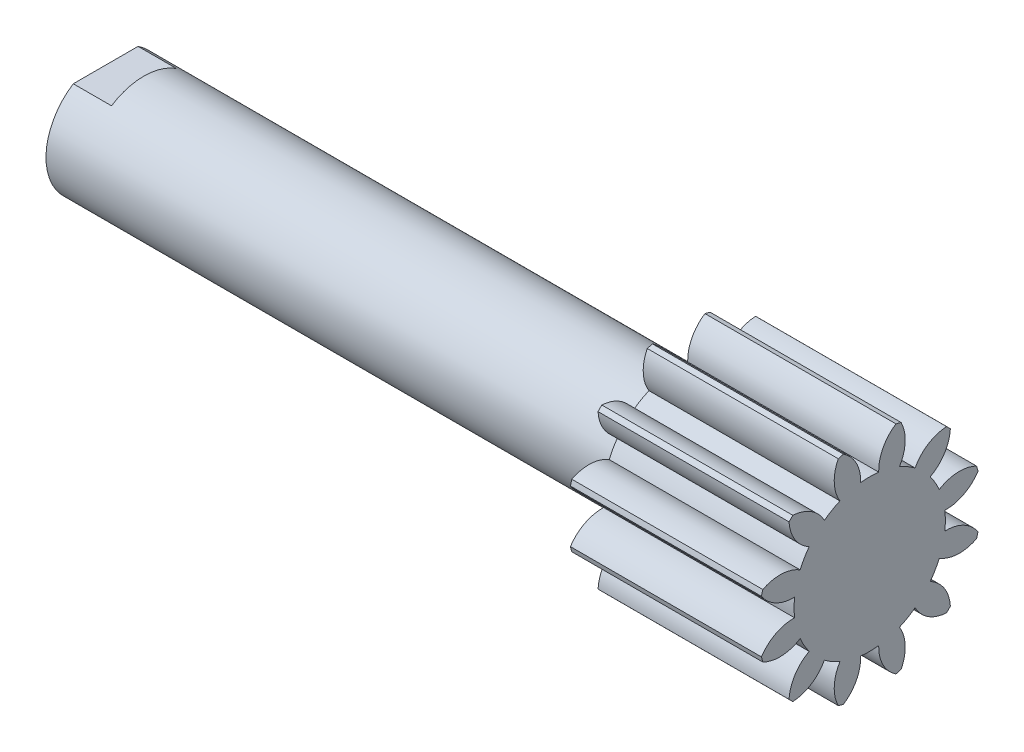
SolidWorks part; units mm, degrees
ref_plane "Plane1" through (0, 0, 0) normal (0, 0, 1) x (1, 0, 0)
ref_plane "Plane2" through (0, 0, 0) normal (0, 1, 0) x (1, 0, 0)
ref_plane "Plane3" through (0, 0, 0) normal (1, 0, 0) x (0, 0, -1)
sketch "HoldingSke" plane through (0, 0, 0) normal (0, 1, 0) x (1, 0, 0)
  line L0 (0, 0) -> (596.2788, -126.743)
  line L1 (-15, 0) -> (100, 0) construction
  line L2 (0, 0) -> (-2.1039, 2.3779)
  line L3 (0, 0) -> (-11.863, 4.5341)
  line L4 (0, 0) -> (8.4473, 1.7955)
  line L5 (0, 0) -> (-47.5972, -17.7524)
  line L6 (0, 0) -> (-10.5278, -7.1032)
  line L7 (-2.1039, 2.3779) -> (8.8314, 51.9901)
  line L8 (-76.2, 54.61) -> (-69.596, 54.61)
  line L9 (-71.009, 38.7566) -> (-53.1078, 45.2721)
  line L10 (-76.2, 71.12) -> (104.1128, 71.12)
  line L11 (0, 0) -> (-12.7, 0)
  line L12 (-76.2, 101.6) -> (-76.1573, 101.6)
  line L13 (24.9733, 27.94) -> (52.9518, 28.4284)
  line L14 (24.9733, 27.94) -> (25.0241, 27.9398)
  line L15 (24.9733, 27.94) -> (100.4021, 29.52)
  circle A0 centre (0, 0) radius 3.175
  circle A1 centre (0, 0) radius 5.0292
  circle A2 centre (0, 0) radius 25.4
  circle A3 centre (0, 0) radius 3.175
  dimension "MHD" = 10.0584
  dimension "Hub_dia" = 50.8
  dimension "Bore" = 6.35
  dimension "MBD" = 6.35
  dimension "Num_teeth" = 12
  dimension "Pitch_radius" = 180.3128
  dimension "Pitch" = 609.6
  dimension "Width" = 12.7
  dimension "Overall_len" = 50.8
  dimension "Show_teeth" = 12
  dimension "Thickness" = 12.7
  dimension "OAL" = 50.8031
  dimension "T_dim" = 6.604
  dimension "Ap" = 20
  dimension "H" = 19.05
  dimension "Backlash" = 0.0427
  dimension "Addendum_fac" = 1
  dimension "Dedendum_fac" = 1.2
  dimension "Clearance_fac" = 0.2
  dimension "Dedendum_add" = 0.0508
sketch "BasProSke" plane through (0, 0, 0) normal (0, 1, 0) x (1, 0, 0)
  line L0 (-10, 0) -> (60, 0) construction
  line L1 (0, 0) -> (0, 7.4083)
  line L2 (0, 0) -> (12.7, 0)
  line L3 (12.7, 0) -> (12.7, 7.4083)
  line L4 (12.7, 7.4083) -> (0, 7.4083)
  dimension "Diameter" = 14.8167
  dimension "Thickness" = 12.7
revolve "Base-Revolve" add sketch "BasProSke" angle 360 about L0
sketch "TooCutSke" plane through (0, 0, 0) normal (1, 0, 0) x (0, 0, -1)
  line L1 (0, 0) -> (0, 107) construction
  line L2 (0, 0) -> (-0.9034, 6.2854) construction
  line L3 (0, 0) -> (-3.2637, 12.1804) construction
  line L4 (-0.9034, 6.2854) -> (-1.6319, 6.0902) construction
  arc A0 (0.5983, 4.9935) -> (-0.5983, 4.9935) centre (0, 0) ccw
  arc A1 (1.7736, 7.219) -> (-1.7736, 7.219) centre (0, 0) ccw
  circle A2 centre (0, 0) radius 6.35 construction
  circle A3 centre (0, 0) radius 5.967 construction
  arc A4 (-0.5983, 4.9935) -> (-1.7736, 7.219) centre (-3.137, 5.0759) ccw
  arc A5 (1.7736, 7.219) -> (0.5983, 4.9935) centre (3.137, 5.0759) ccw
  dimension "Root_dia" = 10.0584
  dimension "Overcut_dia" = 14.8675
  dimension "Pitch_dia" = 12.7
  dimension "Base_dia" = 11.9341
  dimension "Flank_rad" = 2.54
  dimension "Half_ang" = 15
  dimension "Half_CT" = 0.7542
extrude "ToothCut" cut sketch "TooCutSke" along normal through all
pattern_circular "TeethCuts" count 12 every 30 about axis through (-10, 0, 0) along (1, 0, 0) of "ToothCut"
ref_plane "FarPln" through (12.7, 0, 0) normal (1, 0, 0) x (0, 0, -1)
sketch "BorSke" plane through (0, 0, 0) normal (1, 0, 0) x (0, 0, -1)
  circle A0 centre (0, 0) radius 3.9688
  dimension "Diameter" = 7.9375
extrude "Boss-Extrude1" add sketch "BorSke" against normal blind 38.1
sketch "Sketch1" plane through (12.7, 0, 0) normal (1, 0, 0) x (0, 0, -1)
  line L0 (7.1559, 1.9174) -> (4.8578, 1.3017) construction
  circle A0 centre (0, 0) radius 6.2188
  circle A2 centre (0, 0) radius 5.0292 construction
  arc A3 (7.2001, 1.7442) -> (7.1076, 2.0895) centre (0, 0) ccw construction
  arc A4 (4.9935, -0.5983) -> (4.9935, 0.5983) centre (0, 0) ccw construction
  point P10 (6.0069, 1.6095)
sketch "Sketch2" plane through (-38.1, 0, 0) normal (-1, 0, 0) x (0, 0, 1)
  line L0 (0, 0) -> (0, 4.2187) construction
  line L1 (2.1534, 4.6038) -> (-2.1534, 4.6038)
  line L2 (2.1534, 4.6038) -> (2.1534, 3.3337)
  line L3 (2.1534, 3.3337) -> (-2.1534, 3.3337)
  line L4 (-2.1534, 4.6038) -> (-2.1534, 3.3337)
  circle A0 centre (0, 0) radius 3.9688 construction
  point P6 (0, 3.3337)
  point P8 (2.1534, 3.9688)
  point P9 (0, 3.9688)
  dimension "D1" = 1.27
extrude "Cut-Extrude1" cut sketch "Sketch2" against normal blind 2.54
equation "' \"Pitch@HoldingSke\" = 4"
equation "' \"Num_teeth@HoldingSke\" = 12"
equation "' \"Ap@HoldingSke\" =  20"
equation "' \"Width@HoldingSke\" = 0.5"
equation "' \"Hub_dia@HoldingSke\"= 1"
equation "' \"Overall_len@HoldingSke\" = 1.0"
equation "' \"Bore@HoldingSke\" = 0.75"
equation "' \"T_dim@HoldingSke\" = 0.85"
equation "' \"Width@KeySke\" = 0.25"
equation "' \"Show_teeth@HoldingSke\" = 13"
equation "' \"Backlash@HoldingSke\" = 0.009"
equation "' \"Addendum_fac@HoldingSke\" = 1.0"
equation "' \"Dedendum_fac@HoldingSke\" = 1.25"
equation "' \"Dedendum_add@HoldingSke\" = 0.00005"
equation "' \"Clearance_fac@HoldingSke\" = 0.375"
equation "' \"Pitch@HoldingSke\" = 0.5"
equation "' \"Num_teeth@HoldingSke\" = 23"
equation "' \"Show_teeth@HoldingSke\" = 23"
equation "' \"Backlash@HoldingSke\" = 0.0375"
equation "' \"Clearance_fac@HoldingSke\" = 0.25"
equation "\"Overcut_dia@TooCutSke\" = (\"Num_teeth@HoldingSke\" + 2 * \"Addendum_fac@HoldingSke\") / \"Pitch@HoldingSke\" + 0.002"
equation "\"Pitch_dia@TooCutSke\" = \"Num_teeth@HoldingSke\" / \"Pitch@HoldingSke\""
equation "\"Base_dia@TooCutSke\" = \"Num_teeth@HoldingSke\" / \"Pitch@HoldingSke\" * cos((\"Ap@HoldingSke\"  * 3.14159265 / 180))"
equation "\"Root_dia@TooCutSke\" = (\"Num_teeth@HoldingSke\" + 2) / \"Pitch@HoldingSke\" - 2 * (\"Addendum_fac@HoldingSke\" + \"Dedendum_fac@HoldingSke\") / \"Pitch@HoldingSke\" - \"Dedendum_add@HoldingSke\" * 2"
equation "\"Half_ang@TooCutSke\" = 180 / \"Num_teeth@HoldingSke\""
equation "\"Half_CT@TooCutSke\" = \"Num_teeth@HoldingSke\" / \"Pitch@HoldingSke\" * sin((3.14159265 / 2 / \"Num_teeth@HoldingSke\")) / 2 - 7 * \"Backlash@HoldingSke\" / 4"
equation "\"Flank_rad@TooCutSke\" = \"Num_teeth@HoldingSke\" / \"Pitch@HoldingSke\" / 5"
equation "\"Radius@RootFillets\" = \"Clearance_fac@HoldingSke\" / \"Pitch@HoldingSke\" + \"Dedendum_add@HoldingSke\""
equation "\"Break_rad@Breaks\" = 0.02 / \"Pitch@HoldingSke\""
equation "\"Thickness@HoldingSke\" = \"Width@HoldingSke\""
equation "\"OAL@HoldingSke\" = \"Thickness@HoldingSke\""
equation "\"MHD@HoldingSke\" = (\"Num_teeth@HoldingSke\" + 2) / \"Pitch@HoldingSke\" - 2 * (\"Addendum_fac@HoldingSke\" + \"Dedendum_fac@HoldingSke\")  / \"Pitch@HoldingSke\" - \"Dedendum_add@HoldingSke\" * 2"
equation "\"MBD@HoldingSke\" = (\"Num_teeth@HoldingSke\" + 2) / \"Pitch@HoldingSke\" - 2 * (\"Addendum_fac@HoldingSke\" + \"Dedendum_fac@HoldingSke\")  / \"Pitch@HoldingSke\" - \"Dedendum_add@HoldingSke\" * 2 - 0.002"
equation "\"MHD@HoldingSke\" = ((sgn( \"MHD@HoldingSke\" - \"Hub_dia@HoldingSke\" )-1)*( \"MHD@HoldingSke\" - \"Hub_dia@HoldingSke\" ))/-2+ \"Hub_dia@HoldingSke\""
equation "\"MBD@HoldingSke\" = ((sgn( \"MBD@HoldingSke\" - \"Bore@HoldingSke\" )-1)*( \"MBD@HoldingSke\" - \"Bore@HoldingSke\" ))/-2+ \"Bore@HoldingSke\""
equation "\"OAL@HoldingSke\" = ((sgn( \"OAL@HoldingSke\" - \"Overall_len@HoldingSke\" )+1)*( \"OAL@HoldingSke\" - \"Overall_len@HoldingSke\" ))/2 + \"Overall_len@HoldingSke\" + 0.000002"
equation "\"Num_teeth@TeethCuts\" = int( \"Show_teeth@HoldingSke\" ) + 1"
equation "\"Num_teeth@TeethCuts\" = ((sgn( \"Num_teeth@TeethCuts\" - \"Num_teeth@HoldingSke\" )-1)*( \"Num_teeth@TeethCuts\" - \"Num_teeth@HoldingSke\" ))/-2+ \"Num_teeth@HoldingSke\""
equation "\"Num_teeth@TeethCuts\" = ((sgn( \"Num_teeth@TeethCuts\" - 2.0)+1)*( \"Num_teeth@TeethCuts\" - 2.0))/2 +2.0"
equation "\"Angle@TeethCuts\" = 360.0 / \"Num_teeth@HoldingSke\""
equation "\"Diameter@BasProSke\" = (\"Num_teeth@HoldingSke\" + 2 * \"Addendum_fac@HoldingSke\") / \"Pitch@HoldingSke\""
equation "\"Thickness@BasProSke\"  = \"Thickness@HoldingSke\""
equation "' \"Fillet_rad@BasProSke\" =  \"Thickness@HoldingSke\" * 0.05"
equation "\"MHD@HoldingSke\" = ((sgn( \"MHD@HoldingSke\" - \"Root_dia@TooCutSke\" )-1)*( \"MHD@HoldingSke\" - \"Root_dia@TooCutSke\" ))/-2+ \"Root_dia@TooCutSke\""
equation "\"Diameter@HubNeaOneSke\" = \"MHD@HoldingSke\""
equation "\"Length@HubNearOne\" = \"OAL@HoldingSke\" - \"Thickness@BasProSke\""
equation "\"Diameter@HubNeaBotSke\" = \"MHD@HoldingSke\""
equation "\"Length@HubNearBoth\" = ( \"OAL@HoldingSke\" - \"Thickness@BasProSke\" ) / 2.0"
equation "\"Thickness@FarPln\" = \"Thickness@BasProSke\""
equation "\"Diameter@HubFarSke\" = \"MHD@HoldingSke\""
equation "\"Length@HubFar\" = ( \"OAL@HoldingSke\" - \"Thickness@BasProSke\" ) / 2.0"
equation "\"Diameter@BorSke\" = 5 / 16"
equation "\"D1@Bore\" = \"OAL@HoldingSke\" * 2.0"
equation "\"D1@Keyway\" = \"OAL@HoldingSke\" * 2.0"
equation "\"Offset@KeySke\" = \"T_dim@HoldingSke\" - \"MBD@HoldingSke\" / 2.0"
